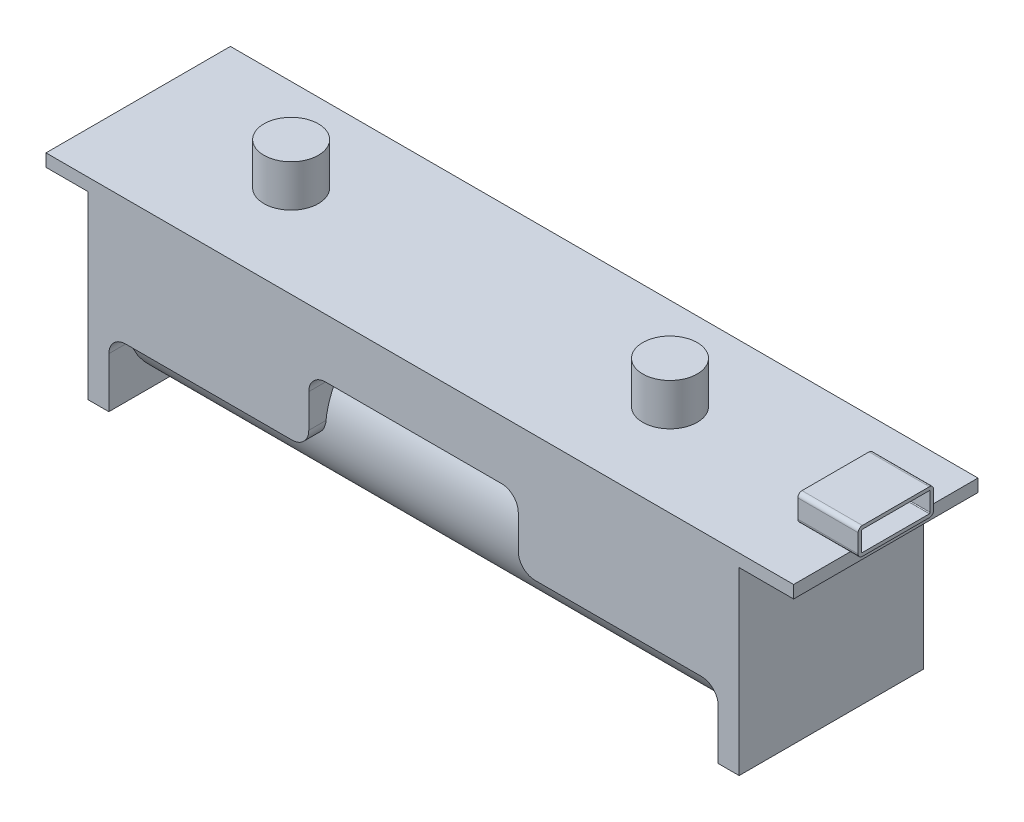
SolidWorks part; units mm, degrees
ref_plane "Front Plane" through (0, 0, 0) normal (0, 0, 1) x (1, 0, 0)
ref_plane "Top Plane" through (0, 0, 0) normal (0, 1, 0) x (1, 0, 0)
ref_plane "Right Plane" through (0, 0, 0) normal (1, 0, 0) x (0, 0, -1)
sketch "Sketch1" plane through (0, 0, 0) normal (0, 1, 0) x (1, 0, 0)
  line L1 (0, 0) -> (89.2, 0)
  line L2 (0, 0) -> (0, 22)
  line L3 (0, 22) -> (89.2, 22)
  line L4 (89.2, 0) -> (89.2, 22)
  dimension "D1" = 89.2
  dimension "D2" = 22
extrude "Boss-Extrude1" add sketch "Sketch1" along normal blind 1.5 contours L2 L1 L4 L3
sketch "Sketch3" plane through (89.2, 0, 0) normal (1, 0, 0) x (0, 0, -1)
  line L0 (0, 1.5) -> (22, 1.5) construction
  line L1 (7, 4.7) -> (15, 4.7)
  line L2 (6.5, 4.2) -> (6.5, 2)
  line L3 (7, 1.5) -> (15, 1.5)
  line L4 (15.5, 4.2) -> (15.5, 2)
  line L5 (7, 4.3) -> (15, 4.3)
  line L6 (15.1, 4.2) -> (15.1, 2)
  line L7 (7, 1.9) -> (15, 1.9)
  line L8 (6.9, 4.2) -> (6.9, 2)
  arc A0 (6.5, 2) -> (7, 1.5) centre (7, 2) ccw
  arc A1 (15, 1.5) -> (15.5, 2) centre (15, 2) ccw
  arc A2 (15, 4.7) -> (15.5, 4.2) centre (15, 4.2) cw
  arc A3 (7, 4.7) -> (6.5, 4.2) centre (7, 4.2) ccw
  arc A4 (15, 4.3) -> (15.1, 4.2) centre (15, 4.2) cw
  arc A5 (15, 1.9) -> (15.1, 2) centre (15, 2) ccw
  arc A6 (6.9, 2) -> (7, 1.9) centre (7, 2) ccw
  arc A7 (7, 4.3) -> (6.9, 4.2) centre (7, 4.2) ccw
  point P6 (6.5, 1.5)
  point P13 (6.5, 4.7)
  point P16 (11, 1.5)
  point P18 (11, 1.5)
  dimension "D3" = 0.5
  dimension "D1" = 9
  dimension "D2" = 3.2
  dimension "D4" = 0.4
extrude "Boss-Extrude2" add sketch "Sketch3" against normal blind 6 and the other way blind 1.2 separate body
sketch "Sketch4" plane through (0, 1.5, 0) normal (0, 1, 0) x (1, 0, 0)
  line L0 (0, 11) -> (89.2, 11) construction
  line L1 (0, 0) -> (0, 22) construction
  line L2 (89.2, 0) -> (89.2, 22) construction
  circle A0 centre (18.25, 11) radius 3.25
  circle A1 centre (63.45, 11) radius 3.25
  point P6 (89.2, 11)
  point P11 (15, 11)
  point P12 (66.7, 11)
  dimension "D1" = 6.5
  dimension "D2" = 22.5
  dimension "D3" = 15
extrude "Boss-Extrude3" add sketch "Sketch4" along normal blind 5 separate body
sketch "Sketch5" plane through (0, 0, 0) normal (0, -1, 0) x (1, 0, 0)
  line L0 (0, 0) -> (89.2, 0) construction
  line L1 (5, 0) -> (82.7, 0)
  line L2 (5, 0) -> (5, -22)
  line L3 (5, -22) -> (82.7, -22)
  line L4 (82.7, 0) -> (82.7, -22)
  line L5 (0, -22) -> (89.2, -22) construction
  line L6 (0, 0) -> (0, -22) construction
  line L7 (89.2, 0) -> (89.2, -22) construction
  dimension "D1" = 5
  dimension "D2" = 6.5
extrude "Boss-Extrude4" add sketch "Sketch5" along normal blind 21.5
sketch "Sketch8" plane through (0, 0, 0) normal (0, 0, 1) x (1, 0, 0)
  line L0 (7.5, -21.5) -> (7.5, -15.5)
  line L1 (82.7, -21.5) -> (5, -21.5) construction
  line L2 (9.5, -13.5) -> (29.35, -13.5)
  line L3 (31.35, -11.5) -> (31.35, -7.5)
  line L4 (33.35, -5.5) -> (54.35, -5.5)
  line L5 (56.35, -7.5) -> (56.35, -11.5)
  line L6 (58.35, -13.5) -> (78.2, -13.5)
  line L7 (80.2, -15.5) -> (80.2, -21.5)
  line L8 (80.2, -21.5) -> (7.5, -21.5)
  line L9 (5, -21.5) -> (5, 0) construction
  line L10 (82.7, -21.5) -> (82.7, 0) construction
  line L11 (0, 1.5) -> (89.2, 1.5) construction
  arc A0 (54.35, -5.5) -> (56.35, -7.5) centre (54.35, -7.5) cw
  arc A1 (31.35, -7.5) -> (33.35, -5.5) centre (33.35, -7.5) cw
  arc A2 (56.35, -11.5) -> (58.35, -13.5) centre (58.35, -11.5) ccw
  arc A3 (31.35, -11.5) -> (29.35, -13.5) centre (29.35, -11.5) cw
  arc A4 (78.2, -13.5) -> (80.2, -15.5) centre (78.2, -15.5) cw
  arc A5 (7.5, -15.5) -> (9.5, -13.5) centre (9.5, -15.5) cw
  point P18 (56.35, -5.5)
  point P21 (31.35, -5.5)
  point P28 (80.2, -13.5)
  dimension "D6" = 2
  dimension "D1" = 2.5
  dimension "D2" = 2.5
  dimension "D3" = 8
  dimension "D4" = 7
  dimension "D5" = 25
extrude "Cut-Extrude1" cut sketch "Sketch8" against normal blind 31.5
ref_plane "Plane1" through (80.2, 0, 0) normal (1, 0, 0) x (0, 0, -1)
sketch "Sketch7" plane through (80.2, 0, 0) normal (1, 0, 0) x (0, 0, -1)
  line L0 (11, 0) -> (11, -12.5) construction
  line L1 (0, 0) -> (22, 0) construction
  line L2 (22, -21.5) -> (0, -21.5) construction
  circle A1 centre (11, -12.5) radius 9
  dimension "D1" = 18
extrude "Boss-Extrude5" add sketch "Sketch7" against normal up to surface (72.7 mm away) separate body up to face at (7.5, -18.5, -11)
